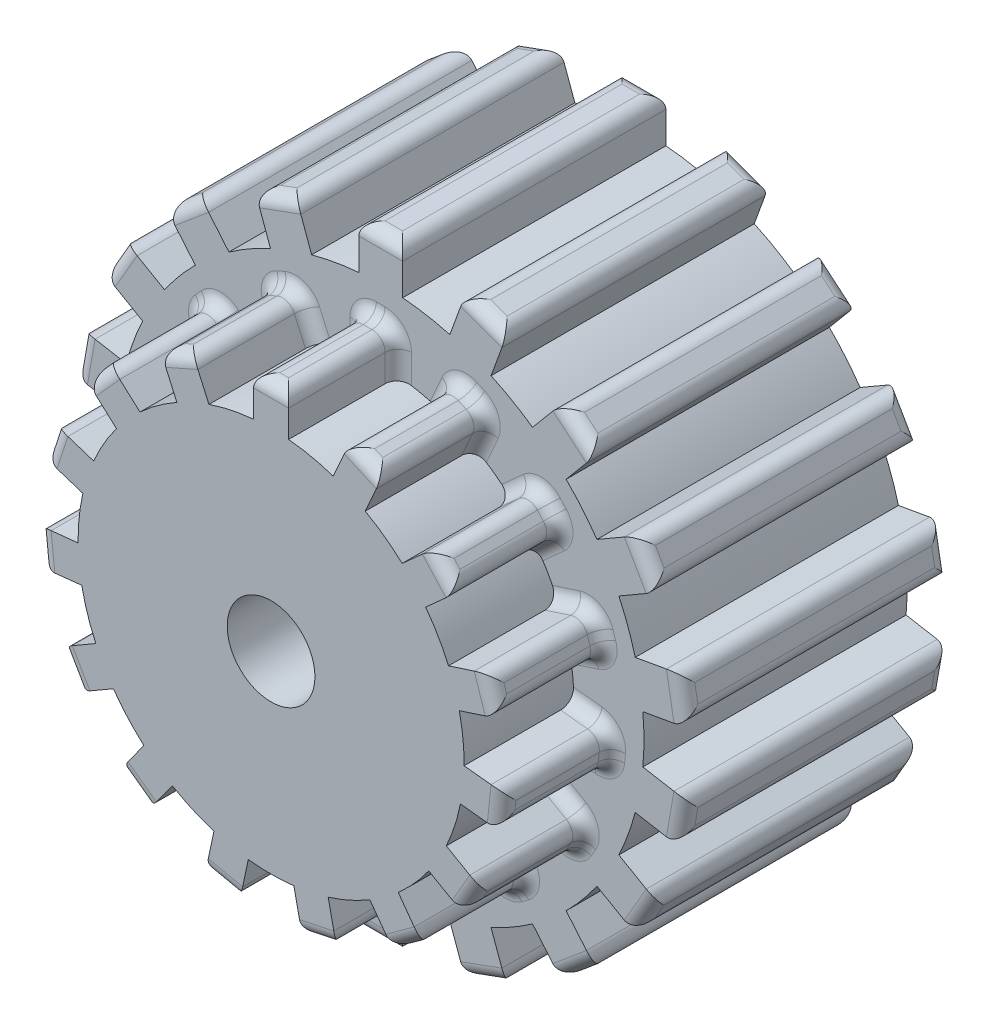
SolidWorks part; units mm, degrees
ref_plane "Front Plane" through (0, 0, 0) normal (0, 0, 1) x (1, 0, 0)
ref_plane "Top Plane" through (0, 0, 0) normal (0, 1, 0) x (1, 0, 0)
ref_plane "Right Plane" through (0, 0, 0) normal (1, 0, 0) x (0, 0, -1)
sketch "Sketch2" plane through (0, 0, 0) normal (0, 0, 1) x (1, 0, 0)
  circle A0 centre (0, 0) radius 60
extrude "Boss-Extrude1" add sketch "Sketch2" along normal blind 60
sketch "Sketch3" plane through (0, 0, 60) normal (0, 0, 1) x (1, 0, 0)
  line L0 (0, 60) -> (0, 70) construction
  line L1 (5, 70) -> (-5, 70)
  line L2 (-5, 70) -> (-5, 59.5215)
  line L3 (-5, 59.5215) -> (5, 59.5215)
  line L4 (5, 59.5215) -> (5, 70)
  circle A0 centre (0, 0) radius 60 construction
  point P9 (0, 70)
extrude "Boss-Extrude2" add sketch "Sketch3" against normal blind 60
fillet "Fillet2" radius 3 4 edges at (-5, 70, 30) (0, 70, 60) (0, 70, 0) (5, 70, 30)
pattern_circular "CirPattern1" count 18 over 360 about axis through (0, 0, 0) along (0, 0, 1) of "Fillet2", "Boss-Extrude2"
sketch "Sketch4" plane through (0, 0, 60) normal (0, 0, 1) x (1, 0, 0)
  circle A0 centre (0, 0) radius 10
extrude "Cut-Extrude1" cut sketch "Sketch4" against normal blind 60
sketch "Sketch5" plane through (0, 0, 60) normal (0, 0, 1) x (1, 0, 0)
  circle A0 centre (0, 0) radius 44
extrude "Boss-Extrude3" add sketch "Sketch5" along normal blind 25
sketch "Sketch6" plane through (0, 0, 85) normal (0, 0, 1) x (1, 0, 0)
  line L0 (0, 44) -> (0, 53) construction
  line L1 (4, 53) -> (-4, 53)
  line L2 (-4, 53) -> (-4, 42.9556)
  line L3 (-4, 42.9556) -> (4, 42.9556)
  line L4 (4, 42.9556) -> (4, 53)
  circle A0 centre (0, 0) radius 44 construction
  circle A1 centre (0, 0) radius 44 construction
  point P10 (0, 53)
extrude "Boss-Extrude4" add sketch "Sketch6" against normal blind 25
sketch "Sketch7" plane through (0, 0, 0) normal (0, 0, -1) x (-1, 0, 0)
  circle A0 centre (0, 0) radius 10
extrude "Cut-Extrude2" cut sketch "Sketch7" against normal blind 90
fillet "Fillet3" radius 3 6 edges at (-4, 48.4089, 60) (4, 48.4089, 60) (-4, 53, 72.5) (0, 53, 85) (0, 53, 60) (4, 53, 72.5)
pattern_circular "CirPattern2" count 15 over 360 about axis through (0, 0, 0) along (0, 0, 1) of "Boss-Extrude4", "Fillet3"
